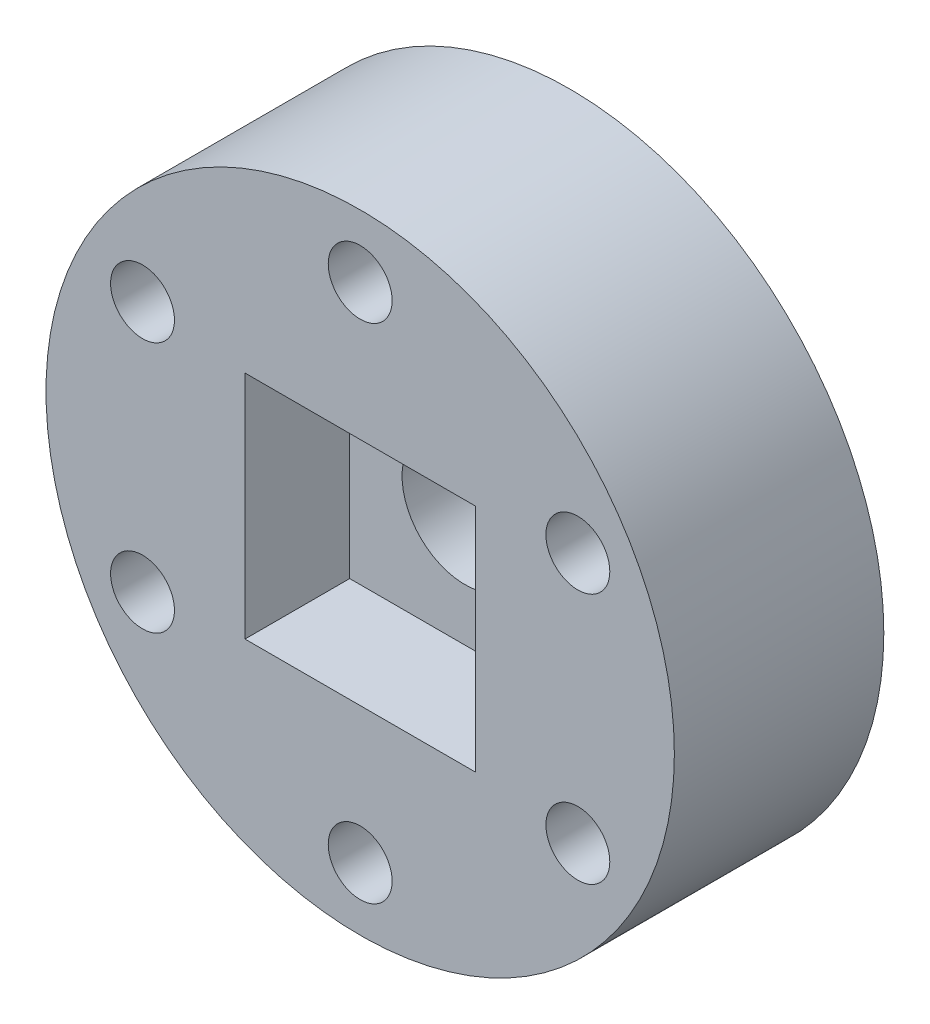
SolidWorks part; units mm, degrees
ref_plane "Спереди" through (0, 0, 0) normal (0, 0, 1) x (1, 0, 0)
ref_plane "Сверху" through (0, 0, 0) normal (0, 1, 0) x (1, 0, 0)
ref_plane "Справа" through (0, 0, 0) normal (1, 0, 0) x (0, 0, -1)
other "Configuration Table"
sketch "Эскиз1" plane through (0, 0, 0) normal (0, 0, 1) x (1, 0, 0)
  circle A0 centre (0, 0) radius 30
  circle A1 centre (0, 0) radius 24 construction
  circle A2 centre (0, 24) radius 3.05
  circle A3 centre (20.7846, 12) radius 3.05
  circle A4 centre (20.7846, -12) radius 3.05
  circle A5 centre (0, -24) radius 3.05
  circle A6 centre (-20.7846, -12) radius 3.05
  circle A7 centre (-20.7846, 12) radius 3.05
  circle A8 centre (0, 0) radius 6
  point P18 (0, 0)
  dimension "D1" = 60
  dimension "D2" = 48
  dimension "D3" = 6.1
  dimension "D5" = 12
  dimension "D4" = 6
extrude "Бобышка-Вытянуть1" add sketch "Эскиз1" along normal blind 20
sketch "Эскиз2" plane through (0, 0, 20) normal (0, 0, 1) x (1, 0, 0)
  line L7 (11, -11) -> (-11, -11)
  line L8 (11, -11) -> (11, 11)
  line L9 (11, 11) -> (-11, 11)
  line L10 (-11, -11) -> (-11, 11)
  line L11 (11, -11) -> (-11, 11) construction
  line L12 (11, 11) -> (-11, -11) construction
  point P0 (0, 0)
  dimension "D1" = 22
extrude "Вырез-Вытянуть1" cut sketch "Эскиз2" against normal blind 10
sketch "Эскиз3" plane through (0, 0, 0) normal (0, 0, -1) x (-1, 0, 0)
  circle A0 centre (0, 24) radius 5.95
  circle A2 centre (20.7846, 12) radius 5.95
  circle A4 centre (20.7846, -12) radius 5.95
  circle A6 centre (0, -24) radius 5.95
  circle A7 centre (0, 0) radius 25 construction
  circle A8 centre (-20.7846, -12) radius 5.95
  circle A9 centre (0, 0) radius 25 construction
  circle A10 centre (-20.7846, 12) radius 5.95
  circle A11 centre (0, 0) radius 25 construction
  point P23 (0, 0)
  dimension "D1" = 11.9
  dimension "D2" = 6
extrude "Вырез-Вытянуть6" cut sketch "Эскиз3" against normal blind 10
